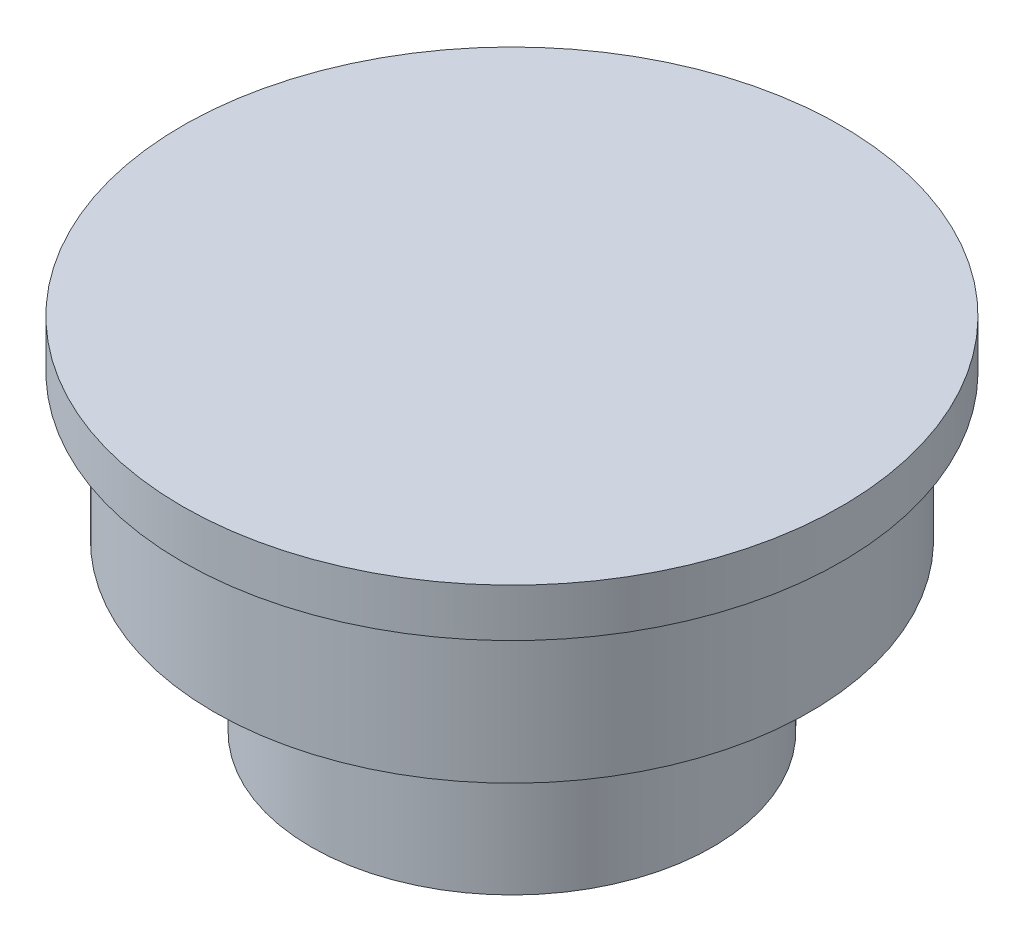
SolidWorks part; units mm, degrees
ref_plane "Front Plane" through (0, 0, 0) normal (0, 0, 1) x (1, 0, 0)
ref_plane "Top Plane" through (0, 0, 0) normal (0, 1, 0) x (1, 0, 0)
ref_plane "Right Plane" through (0, 0, 0) normal (1, 0, 0) x (0, 0, -1)
sketch "Sketch1" plane through (0, 0, 0) normal (0, 0, 1) x (1, 0, 0)
  line L0 (0, 0) -> (12.125, 0)
  line L1 (12.125, 0) -> (12.125, 10)
  line L2 (19.9, 18.8) -> (18, 18.8)
  line L3 (19.9, 18.8) -> (19.9, 21.7)
  line L4 (19.9, 21.7) -> (0, 21.7)
  line L5 (18, 18.8) -> (18, 10)
  line L6 (18, 10) -> (12.125, 10)
  line L7 (0, 21.7) -> (0, 0) construction
  line L8 (0, 0) -> (0, 21.7)
  dimension "D1" = 12.125
  dimension "D2" = 21.7
  dimension "D3" = 2.9
  dimension "D4" = 18
  dimension "D5" = 19.9
  dimension "D6" = 10
revolve "Revolve1" add sketch "Sketch1" angle 360 about L7
